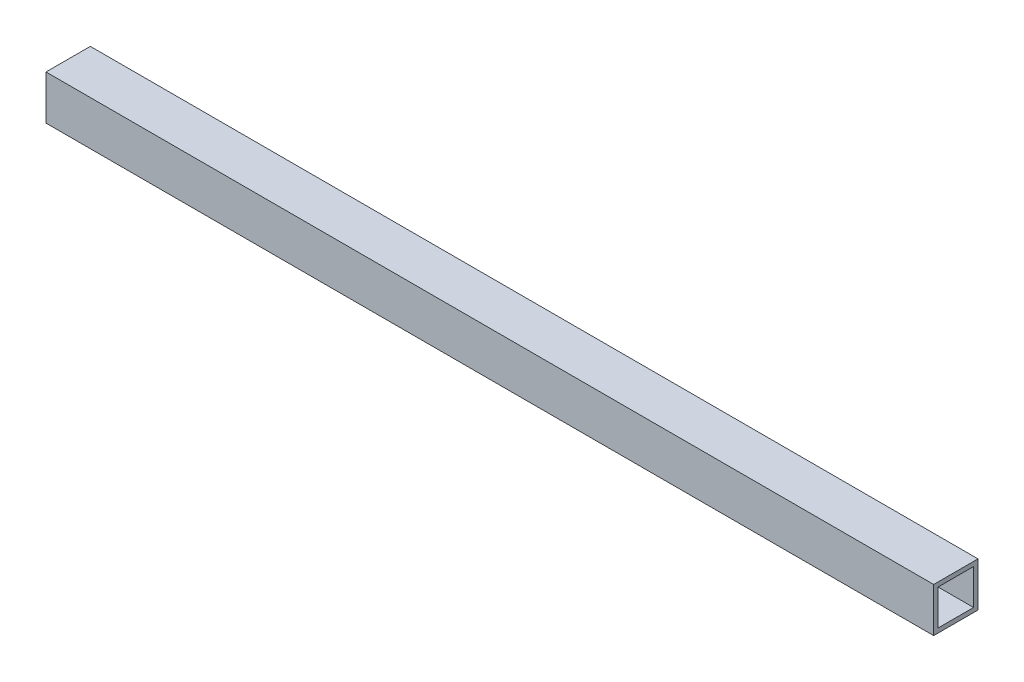
SolidWorks part; units mm, degrees
material "6061 合金"
ref_plane "前视基准面" through (0, 0, 0) normal (0, 0, 1) x (1, 0, 0)
ref_plane "上视基准面" through (0, 0, 0) normal (0, 1, 0) x (1, 0, 0)
ref_plane "右视基准面" through (0, 0, 0) normal (1, 0, 0) x (0, 0, -1)
sketch "草图1" plane through (0, 0, 0) normal (0, 0, 1) x (1, 0, 0)
  line L0 (0, 0) -> (400.5, 0)
  dimension "D1" = 400.5
other "方形管 20 X 20 X 2 无圆角(1)"
ref_plane "基准面1" through (0, 0, 0) normal (1, 0, 0) x (0, 1, 0)
sketch "Sketch1" plane through (0, 0, 0) normal (1, 0, 0) x (0, 1, 0)
  line L1 (10, -10) -> (-10, -10)
  line L2 (10, -10) -> (10, 10)
  line L3 (10, 10) -> (-10, 10)
  line L4 (-10, -10) -> (-10, 10)
  line L5 (10, -10) -> (-10, 10) construction
  line L6 (10, 10) -> (-10, -10) construction
  line L7 (8, -8) -> (-8, -8)
  line L8 (8, -8) -> (8, 8)
  line L9 (8, 8) -> (-8, 8)
  line L10 (-8, -8) -> (-8, 8)
  line L11 (8, -8) -> (-8, 8) construction
  line L12 (8, 8) -> (-8, -8) construction
  point P0 (-10, 0)
  point P1 (10, 0)
  point P2 (0, 10)
  point P3 (0, -10)
  point P4 (0, 0)
  point P5 (-10, -10)
  point P6 (10, -10)
  point P7 (10, 10)
  point P8 (-10, 10)
  point P9 (0, 0)
  point P14 (0, 0)
  point P19 (0, 0)
  dimension "D1" = 20
  dimension "D2" = 2
